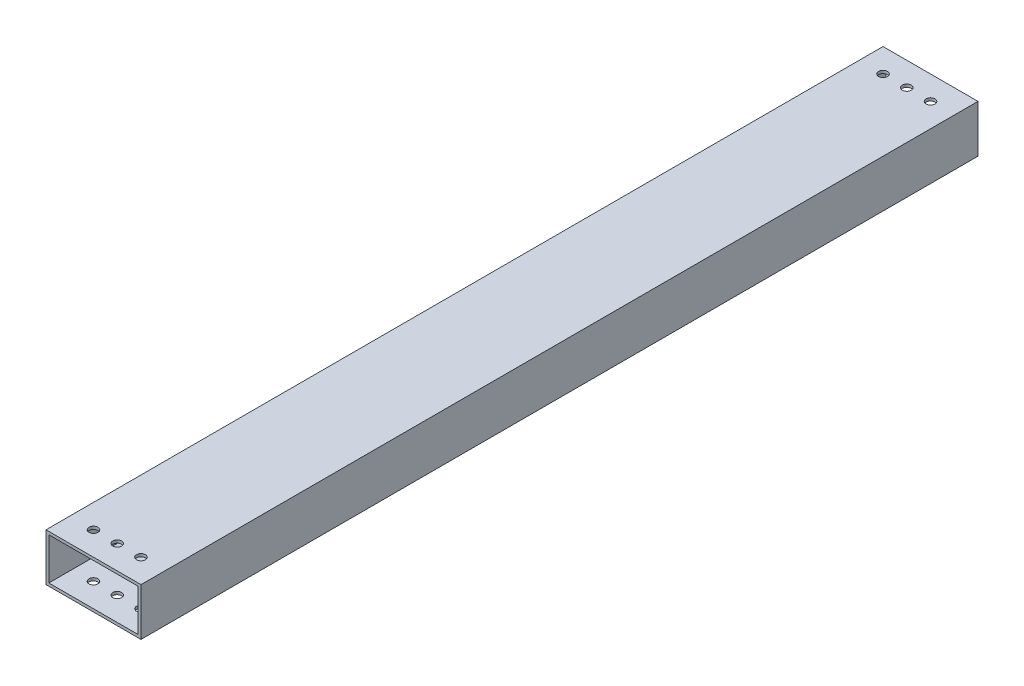
SolidWorks part; units mm, degrees
ref_plane "Front Plane" through (0, 0, 0) normal (0, 0, 1) x (1, 0, 0)
ref_plane "Top Plane" through (0, 0, 0) normal (0, 1, 0) x (1, 0, 0)
ref_plane "Right Plane" through (0, 0, 0) normal (1, 0, 0) x (0, 0, -1)
sketch "Sketch1" plane through (0, 0, 0) normal (0, 0, 1) x (1, 0, 0)
  line L1 (0, 0) -> (-50.8, 0)
  line L2 (0, 0) -> (0, 25.4)
  line L3 (0, 25.4) -> (-50.8, 25.4)
  line L4 (-50.8, 0) -> (-50.8, 25.4)
  dimension "D1" = 50.8
  dimension "D2" = 25.4
extrude "Extrude-Thin1" add sketch "Sketch1" along normal blind 447.675 thin contours L3 L4 L1 L2
sketch "Sketch2" plane through (0, 25.4, 0) normal (0, 1, 0) x (1, 0, 0)
  line L0 (-128.8676, -223.8375) -> (115.1597, -223.8375)
  line L1 (0, -447.675) -> (0, 0) construction
  line L2 (0, -447.675) -> (-50.8, -447.675) construction
  line L3 (0, 0) -> (-50.8, 0) construction
  circle A0 centre (-38.1, -434.975) radius 2.3813
  circle A1 centre (-25.4, -434.975) radius 2.3813
  circle A3 centre (-12.7, -434.975) radius 2.3813
  circle A4 centre (-38.1, -12.7) radius 2.3813
  circle A5 centre (-12.7, -12.7) radius 2.3813
  circle A6 centre (-25.4, -12.7) radius 2.3813
  dimension "D1" = 4.7625
  dimension "D2" = 4.7625
  dimension "D3" = 4.7625
  dimension "D5" = 12.7
  dimension "D6" = 12.7
  dimension "D7" = 12.7
  dimension "D4" = 12.7
  dimension "D8" = 223.8375
extrude "Cut-Extrude1" cut sketch "Sketch2" against normal through all both and the other way through all contours A0 | A1 | A3 | A4 | A6 | A5
